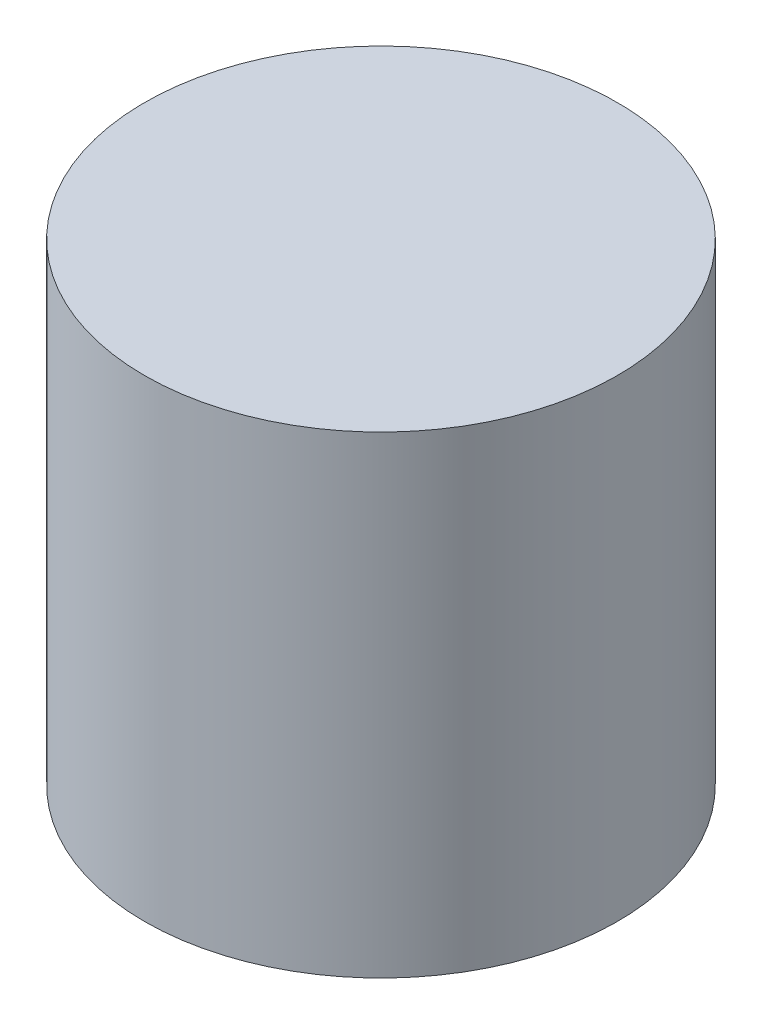
SolidWorks part; units mm, degrees
material "7079 Alloy"
ref_plane "Front Plane"
ref_plane "Top Plane" through (0, 0, 0) normal (0, 1, 0) x (1, 0, 0)
ref_plane "Right Plane" through (0, 0, 0) normal (1, 0, 0) x (0, 0, -1)
sketch "Sketch1" plane through (0, 0, 0) normal (0, 1, 0) x (1, 0, 0)
  circle A0 centre (0, 0) radius 50
  dimension "D1" = 100
extrude "Boss-Extrude1" add sketch "Sketch1" along normal blind 100 contours A0
